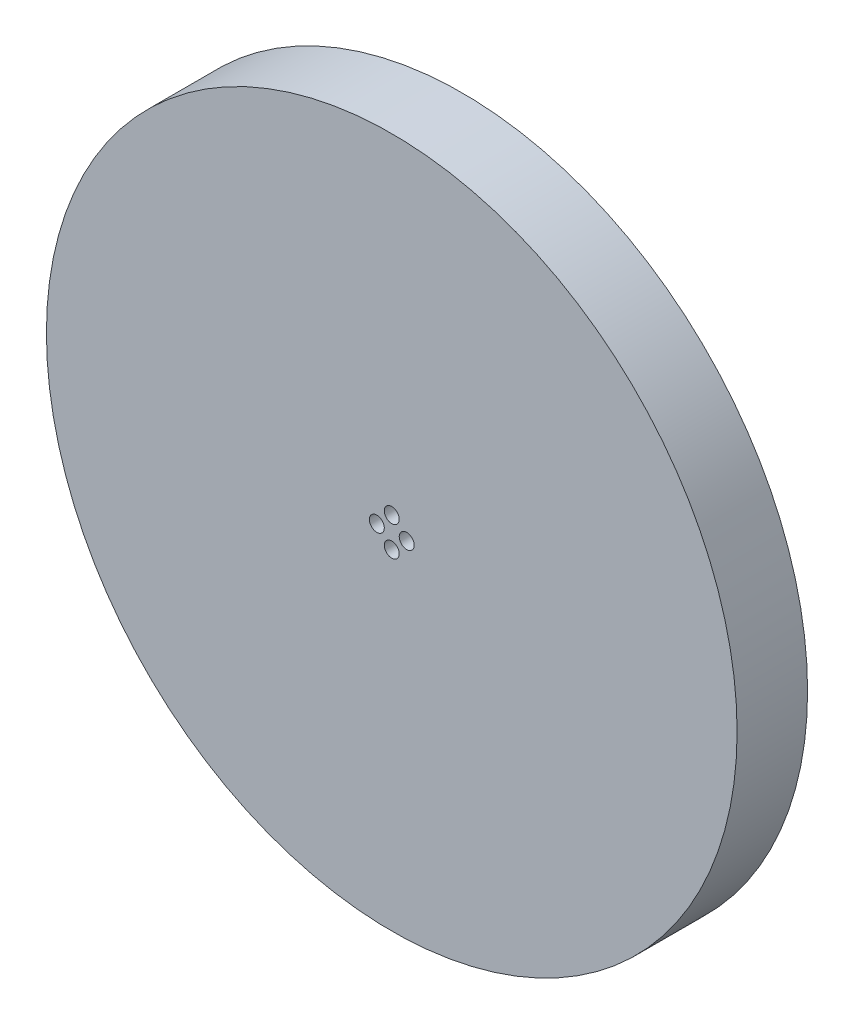
SolidWorks part; units mm, degrees
ref_plane "Plan de face" through (0, 0, 0) normal (0, 0, 1) x (1, 0, 0)
ref_plane "Plan de dessus" through (0, 0, 0) normal (0, 1, 0) x (1, 0, 0)
ref_plane "Plan de droite" through (0, 0, 0) normal (1, 0, 0) x (0, 0, -1)
sketch "Esquisse1" plane through (0, 0, 0) normal (0, 0, 1) x (1, 0, 0)
  circle A0 centre (0, 0) radius 24.5
  dimension "D1" = 49
extrude "Boss.-Extru.1" add sketch "Esquisse1" along normal blind 5
sketch "Esquisse2" plane through (0, 0, 5) normal (0, 0, 1) x (1, 0, 0)
  line L0 (0, 0) -> (0, 2.1842) construction
  circle A0 centre (0, 1.06) radius 0.53
  dimension "D2" = 1.06
  dimension "D1" = 1.06
extrude "Enlèv. mat.-Extru.1" cut sketch "Esquisse2" against normal up to surface (5 mm away) up to face at (24.5, 0, 0)
pattern_circular "Répétition circulaire1" count 4 over 360 about axis through (0, 0, 0) along (0, 0, 1) of "Enlèv. mat.-Extru.1"
